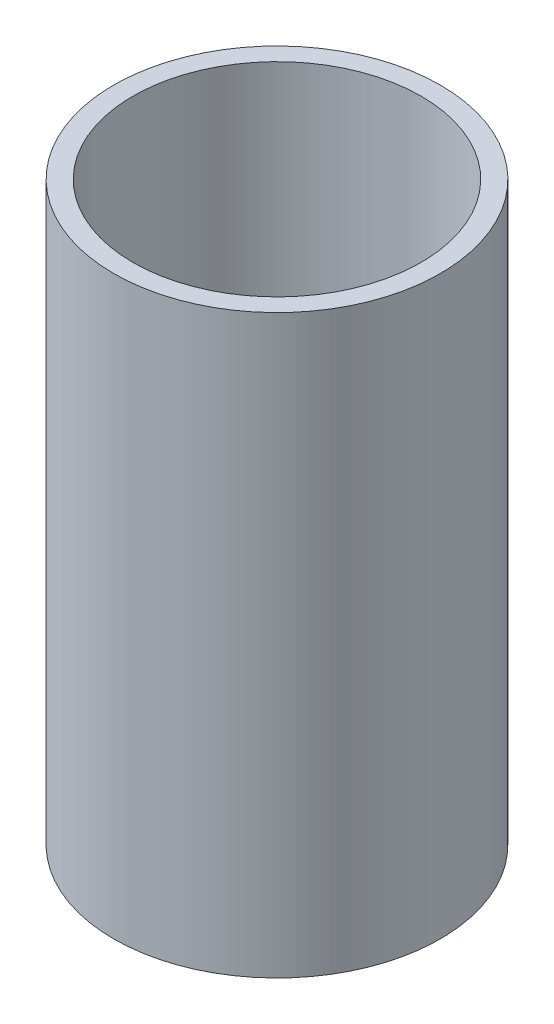
SolidWorks part; units mm, degrees
ref_plane "Front Plane" through (0, 0, 0) normal (0, 0, 1) x (1, 0, 0)
ref_plane "Top Plane" through (0, 0, 0) normal (0, 1, 0) x (1, 0, 0)
ref_plane "Right Plane" through (0, 0, 0) normal (1, 0, 0) x (0, 0, -1)
sketch "Sketch3" plane through (0, 0, 0) normal (0, 1, 0) x (1, 0, 0)
  circle A0 centre (0, 0) radius 17
  circle A1 centre (0, 0) radius 15
extrude "Boss-Extrude1" add sketch "Sketch3" along normal blind 60
